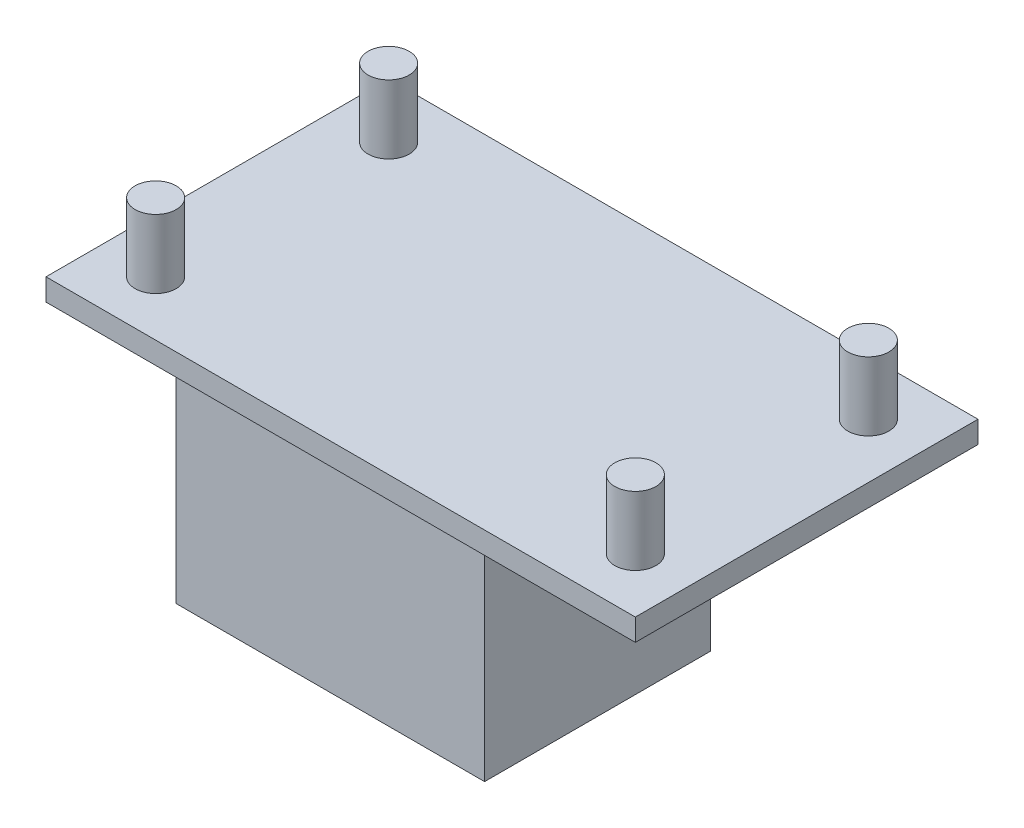
SolidWorks part; units mm, degrees
ref_plane "Front Plane" through (0, 0, 0) normal (0, 0, 1) x (1, 0, 0)
ref_plane "Top Plane" through (0, 0, 0) normal (0, 1, 0) x (1, 0, 0)
ref_plane "Right Plane" through (0, 0, 0) normal (1, 0, 0) x (0, 0, -1)
sketch "SK_P01_Standoff" plane through (0, 0, 0) normal (0, 1, 0) x (1, 0, 0)
  circle A0 centre (-17.5, 8.5) radius 1.5
extrude "P01_Standoff" add sketch "SK_P01_Standoff" along normal blind 5 from offset 20.4
sketch "SK_P02_Standoff" plane through (0, 0, 0) normal (0, 1, 0) x (1, 0, 0)
  circle A0 centre (-17.5, -8.5) radius 1.5
extrude "P02_Standoff" add sketch "SK_P02_Standoff" along normal blind 5 from offset 20.4
sketch "SK_P03_Standoff" plane through (0, 0, 0) normal (0, 1, 0) x (1, 0, 0)
  circle A0 centre (17.5, 8.5) radius 1.5
extrude "P03_Standoff" add sketch "SK_P03_Standoff" along normal blind 5 from offset 20.4
sketch "SK_P04_Standoff" plane through (0, 0, 0) normal (0, 1, 0) x (1, 0, 0)
  circle A0 centre (17.5, -8.5) radius 1.5
extrude "P04_Standoff" add sketch "SK_P04_Standoff" along normal blind 5 from offset 20.4
sketch "SK_P05_PololuRCswitchwithrelay" plane through (0, 0, 0) normal (0, 1, 0) x (1, 0, 0)
  line L0 (-21.5, -12.5) -> (21.5, -12.5)
  line L1 (21.5, -12.5) -> (21.5, 12.5)
  line L2 (21.5, 12.5) -> (-21.5, 12.5)
  line L3 (-21.5, 12.5) -> (-21.5, -12.5)
extrude "P05_PololuRCswitchwithrelay" add sketch "SK_P05_PololuRCswitchwithrelay" along normal blind 1.6 from offset 18.8
sketch "SK_P06_RelayG5LE" plane through (0, 0, 0) normal (0, 1, 0) x (1, 0, 0)
  line L0 (-16.5, -8) -> (6, -8)
  line L1 (6, -8) -> (6, 8.5)
  line L2 (6, 8.5) -> (-16.5, 8.5)
  line L3 (-16.5, 8.5) -> (-16.5, -8)
extrude "P06_RelayG5LE" add sketch "SK_P06_RelayG5LE" along normal blind 18.8
